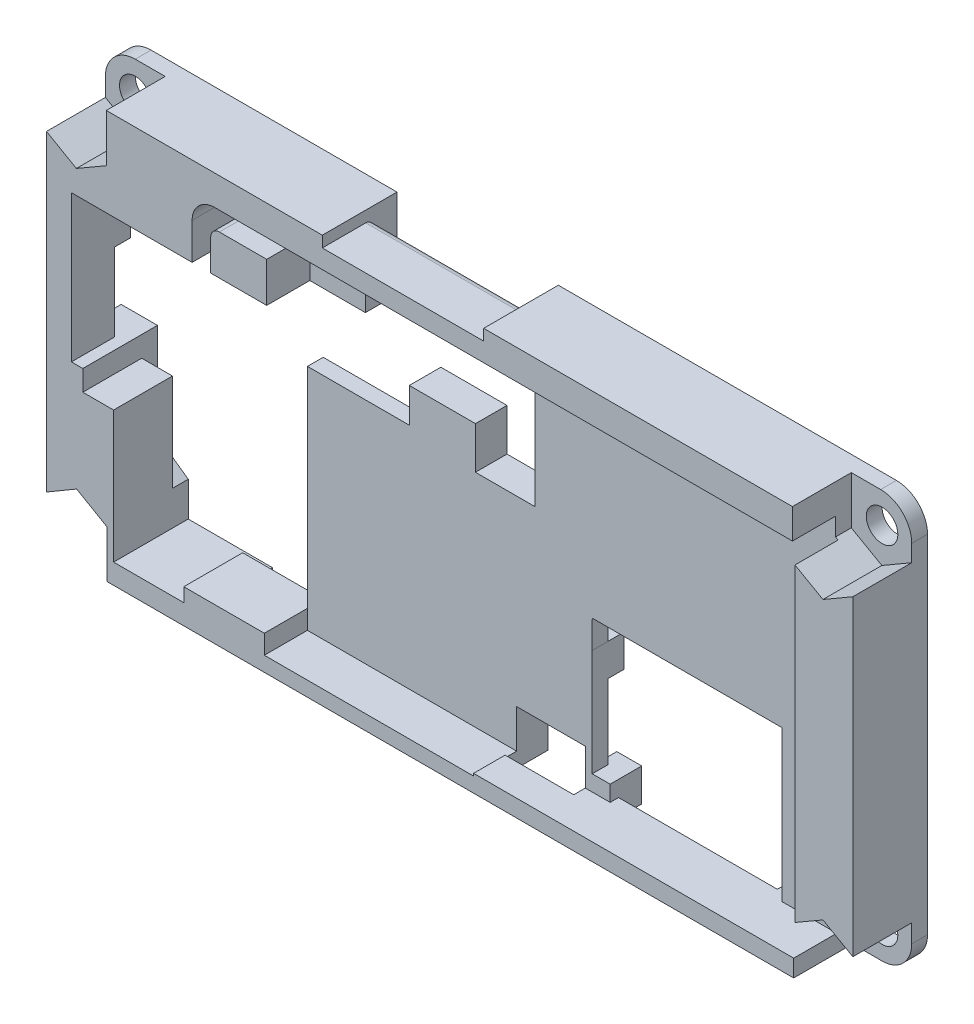
SolidWorks part; units mm, degrees
ref_plane "前视基准面" through (0, 0, 0) normal (0, 0, 1) x (1, 0, 0)
ref_plane "上视基准面" through (0, 0, 0) normal (0, 1, 0) x (1, 0, 0)
ref_plane "右视基准面" through (0, 0, 0) normal (1, 0, 0) x (0, 0, -1)
other "Configuration Table"
sketch "草图1" plane through (0, 0, 0) normal (0, 0, 1) x (1, 0, 0)
  line L0 (42.3742, 38.777) -> (73.7375, 38.777)
  line L1 (2.8575, 38.777) -> (73.7375, 38.777) construction
  line L2 (76.6955, 35.8191) -> (76.6955, 2.8364)
  line L3 (73.8718, 0.0127) -> (65.8565, 0.0127)
  line L4 (73.8718, 0.0127) -> (2.882, 0.0127) construction
  line L5 (65.8565, 0.0127) -> (65.8565, 13.0447)
  line L6 (65.8565, 13.0447) -> (70.1007, 13.0447)
  line L7 (70.1007, 13.0447) -> (70.1007, 20.0542)
  line L8 (70.1007, 20.0542) -> (44.7517, 20.0542)
  line L9 (44.7517, 22.4295) -> (44.7517, 32.4704)
  line L10 (44.7517, 32.4704) -> (42.3742, 32.4704)
  line L11 (42.3742, 32.4704) -> (42.3742, 38.777)
  line L12 (20.8324, 0.0127) -> (2.882, 0.0127)
  line L13 (0.0127, 2.882) -> (0.0127, 16.4108)
  line L14 (0.0127, 2.882) -> (0.0127, 35.9322) construction
  line L15 (0.0127, 16.4108) -> (3.4684, 16.4108)
  line L16 (3.4684, 16.4108) -> (3.4684, 7.2908)
  line L17 (3.4684, 7.2908) -> (6.395, 5.2037)
  line L18 (6.395, 5.2037) -> (6.395, 1.925)
  line L19 (6.395, 1.925) -> (14.4152, 1.925)
  line L20 (14.4152, 1.925) -> (14.4152, 1.4675)
  line L21 (14.4152, 1.4675) -> (20.8324, 1.4675)
  line L23 (2.8575, 38.777) -> (26.2427, 38.777)
  line L24 (26.2427, 38.777) -> (26.2427, 30.3451)
  line L25 (26.2427, 30.3451) -> (2.3856, 30.3451)
  line L26 (2.3856, 30.3451) -> (2.3856, 30.8342)
  line L27 (2.3856, 30.8342) -> (0.0127, 30.8342)
  line L28 (0.0127, 30.8342) -> (0.0127, 35.9322)
  line L29 (30.4158, 26.4371) -> (36.7059, 26.4371)
  line L30 (42.3742, 13.309) -> (47.8085, 13.309)
  line L31 (42.3742, 13.309) -> (42.3742, 10.2399)
  line L32 (42.3742, 10.2399) -> (47.8085, 10.2399)
  line L33 (47.8085, 13.309) -> (47.8085, 10.2399)
  line L34 (49.5154, 3.1504) -> (47.1508, 3.1504)
  line L35 (49.5154, 3.1504) -> (49.5154, 0.0127)
  line L36 (49.5154, 0.0127) -> (47.1508, 0.0127)
  line L37 (47.1508, 3.1504) -> (47.1508, 0.0127)
  line L38 (36.7059, 26.4371) -> (36.7059, 22.4295)
  line L39 (36.7059, 22.4295) -> (44.7517, 22.4295)
  line L40 (44.7517, 20.0542) -> (44.7517, 16.7907)
  line L41 (44.7517, 16.7907) -> (30.4158, 16.7907)
  line L42 (30.4158, 16.7907) -> (30.4158, 26.4371)
  line L44 (33.5959, 0.0127) -> (40.6267, 0.0127)
  line L45 (33.5959, 1.4675) -> (33.5959, 4.6376)
  line L46 (33.5959, 4.6376) -> (40.6267, 4.6376)
  line L47 (40.6267, 0.0127) -> (40.6267, 4.6376)
  line L48 (33.5959, 0.0127) -> (20.8324, 0.0127)
  line L50 (33.5959, 1.4675) -> (20.8324, 1.4675)
  arc A0 (73.7375, 38.777) -> (76.6955, 35.8191) centre (73.7375, 35.8191) cw
  arc A1 (76.6955, 2.8364) -> (73.8718, 0.0127) centre (73.8718, 2.8364) cw
  circle A2 centre (73.8718, 2.882) radius 1.5
  circle A3 centre (73.8718, 35.8941) radius 1.5
  arc A4 (2.882, 0.0127) -> (0.0127, 2.882) centre (2.882, 2.882) cw
  circle A5 centre (2.9024, 2.882) radius 1.5
  arc A6 (0.0127, 35.9322) -> (2.8575, 38.777) centre (2.8575, 35.9322) cw
  circle A7 centre (2.8575, 35.8776) radius 1.5
  dimension "D1" = 3
  dimension "D2" = 3
  dimension "D3" = 3
  dimension "D4" = 3
extrude "凸台-拉伸1" add sketch "草图1" along normal blind 1.5
sketch "草图3" plane through (0, 0, 1.5) normal (0, 0, 1) x (1, 0, 0)
  line L0 (0.0127, 35.9322) -> (0.0127, 30.8342) construction
  line L1 (26.2427, 38.777) -> (2.8575, 38.777) construction
  line L2 (0.0127, 34.2052) -> (0.0127, 30.8342)
  line L3 (26.2427, 38.777) -> (5.7019, 38.777)
  line L4 (26.2427, 38.777) -> (26.2427, 30.3451)
  line L5 (26.2427, 30.3451) -> (2.3856, 30.3451)
  line L6 (2.3856, 30.3451) -> (2.3856, 23.8174)
  line L7 (2.3856, 23.8174) -> (0.0127, 23.8174)
  line L8 (0.0127, 2.882) -> (0.0127, 35.9322) construction
  line L9 (0.0127, 23.8174) -> (0.0127, 30.8342)
  line L10 (5.7019, 38.777) -> (5.7019, 34.2258)
  line L11 (5.7019, 34.2258) -> (2.8575, 32.5779)
  line L12 (2.8575, 32.5779) -> (0.0127, 34.2052)
  line L13 (42.3742, 38.777) -> (70.9493, 38.777)
  line L14 (73.7375, 38.777) -> (42.3742, 38.777) construction
  line L15 (70.9493, 38.777) -> (70.9493, 34.2258)
  line L16 (70.9493, 34.2258) -> (73.8524, 32.5779)
  line L17 (73.8524, 32.5779) -> (76.6955, 34.2258)
  line L18 (76.6955, 35.8191) -> (76.6955, 2.8364) construction
  line L19 (76.6955, 34.2258) -> (76.6955, 4.5742)
  line L20 (76.6955, 2.8364) -> (76.6955, 35.8191) construction
  line L21 (76.6955, 4.5742) -> (73.8524, 6.188)
  line L22 (73.8524, 6.188) -> (71.0683, 4.5742)
  line L23 (71.0683, 4.5742) -> (71.0683, 0.0127)
  line L24 (65.8565, 0.0127) -> (73.8718, 0.0127) construction
  line L25 (71.0683, 0.0127) -> (65.8565, 0.0127)
  line L26 (65.8565, 0.0127) -> (65.8565, 13.0447)
  line L27 (65.8565, 13.0447) -> (65.8565, 15.9725)
  line L28 (65.8565, 15.9725) -> (47.8131, 15.9725)
  line L29 (47.8131, 15.9725) -> (47.8085, 13.309)
  line L30 (47.8085, 13.309) -> (47.8085, 3.1504)
  line L31 (49.5154, 3.1504) -> (47.1508, 3.1504) construction
  line L32 (47.8085, 3.1504) -> (49.5154, 3.1504)
  line L33 (49.5154, 3.1504) -> (49.5154, 0.0127)
  line L34 (49.5154, 0.0127) -> (47.1508, 0.0127)
  line L35 (47.1508, 0.0127) -> (47.1508, 5.0962)
  line L36 (47.1508, 5.0962) -> (42.3742, 5.0962)
  line L39 (0.0127, 16.4108) -> (3.4684, 16.4108)
  line L40 (3.4684, 16.4108) -> (0.0127, 16.4108) construction
  line L41 (3.4684, 16.4108) -> (3.4684, 14.453)
  line L42 (3.4684, 7.2908) -> (3.4684, 16.4108) construction
  line L43 (3.4684, 14.453) -> (6.395, 14.453)
  line L44 (6.395, 14.453) -> (6.395, 10.1048)
  line L45 (6.395, 10.1048) -> (6.395, 5.2037)
  line L46 (6.395, 5.2037) -> (6.395, 1.925)
  line L47 (6.395, 1.925) -> (13.0684, 1.925)
  line L48 (14.4152, 1.925) -> (6.395, 1.925) construction
  line L49 (13.0684, 1.925) -> (13.0684, 3.2369)
  line L50 (13.0684, 3.2369) -> (20.728, 3.2369)
  line L52 (40.0567, 0.0127) -> (5.7831, 0.0127)
  line L53 (2.882, 0.0127) -> (40.6267, 0.0127) construction
  line L54 (5.7831, 0.0127) -> (5.7831, 4.506)
  line L55 (5.7831, 4.506) -> (2.882, 6.188)
  line L56 (2.882, 6.188) -> (0.0127, 4.506)
  line L57 (0.0127, 4.506) -> (0.0127, 16.4108)
  line L58 (42.3742, 22.4295) -> (36.7059, 22.4295)
  line L59 (44.7517, 22.4295) -> (36.7059, 22.4295) construction
  line L60 (36.7059, 22.4295) -> (36.7059, 26.4371)
  line L61 (36.7059, 26.4371) -> (30.4158, 26.4371)
  line L62 (30.4158, 26.4371) -> (30.4158, 23.1633)
  line L66 (42.3742, 22.4295) -> (42.3742, 38.777)
  line L67 (40.6267, 0.0127) -> (40.6267, 4.6376)
  line L68 (40.6267, 4.6376) -> (40.6267, 5.0962)
  line L69 (40.6267, 5.0962) -> (42.3742, 5.0962)
  line L70 (40.0567, 0.0127) -> (40.6267, 0.0127)
  line L71 (20.728, 3.2369) -> (20.728, 23.1633)
  line L72 (32.6413, 23.1633) -> (15.9072, 23.1633) construction
  line L73 (20.728, 23.1633) -> (30.4158, 23.1633)
extrude "凸台-拉伸2" add sketch "草图3" along normal blind 1.5
sketch "草图5" plane through (0, 0, 3) normal (0, 0, 1) x (1, 0, 0)
  line L0 (42.3742, 38.777) -> (42.3742, 22.4295) construction
  line L1 (70.9493, 38.777) -> (42.3742, 38.777)
  line L2 (70.9493, 38.777) -> (70.9493, 35.9391)
  line L3 (70.9493, 35.9391) -> (42.3742, 35.9391)
  line L4 (42.3742, 38.777) -> (42.3742, 35.9391)
  line L5 (76.6955, 34.2258) -> (73.8524, 32.5779)
  line L6 (73.8524, 32.5779) -> (71.1891, 34.0897)
  line L7 (73.8524, 32.5779) -> (70.9493, 34.2258) construction
  line L8 (71.1891, 34.0897) -> (71.1891, 4.6442)
  line L9 (71.0683, 4.5742) -> (73.8524, 6.188) construction
  line L10 (71.1891, 4.6442) -> (73.8524, 6.188)
  line L11 (73.8524, 6.188) -> (76.6955, 4.5742)
  line L12 (76.6955, 4.5742) -> (76.6955, 34.2258)
  line L13 (47.1508, 5.0962) -> (47.1508, 0.0127) construction
  line L14 (71.0683, 0.0127) -> (47.1508, 0.0127)
  line L15 (71.0683, 0.0127) -> (71.0683, 1.6475)
  line L16 (71.0683, 1.6475) -> (47.1508, 1.6475)
  line L17 (47.1508, 0.0127) -> (47.1508, 1.6475)
  line L19 (40.6267, 0.0127) -> (6.395, 0.0127)
  line L20 (40.6267, 0.0127) -> (40.6267, 1.423)
  line L21 (40.6267, 1.423) -> (20.728, 1.423)
  line L23 (6.395, 1.925) -> (13.0684, 1.925)
  line L24 (13.0684, 1.925) -> (13.0684, 3.2369)
  line L25 (13.0684, 3.2369) -> (20.728, 3.2369)
  line L26 (20.728, 3.2369) -> (20.728, 1.423)
  line L27 (26.2427, 38.777) -> (26.2427, 35.9391)
  line L28 (26.2427, 30.3451) -> (26.2427, 38.777) construction
  line L29 (26.2427, 35.9391) -> (20.9533, 35.9391)
  line L30 (20.9533, 35.9391) -> (20.9533, 30.3451)
  line L31 (2.3856, 30.3451) -> (26.2427, 30.3451) construction
  line L32 (20.9533, 30.3451) -> (2.3856, 30.3451)
  line L33 (2.3856, 30.3451) -> (2.3856, 23.8174)
  line L35 (0.0127, 23.8174) -> (0.0127, 34.2052)
  line L36 (0.0127, 34.2052) -> (2.8575, 32.5779)
  line L37 (2.8575, 32.5779) -> (5.7019, 34.2258)
  line L38 (5.7019, 34.2258) -> (5.7019, 38.777)
  line L39 (5.7019, 38.777) -> (26.2427, 38.777)
  line L40 (6.395, 0.0127) -> (5.7831, 0.0127)
  line L41 (5.7831, 0.0127) -> (5.7831, 4.506)
  line L42 (5.7831, 4.506) -> (2.882, 6.188)
  line L43 (2.882, 6.188) -> (0.0127, 4.506)
  line L44 (0.0127, 4.506) -> (0.0127, 16.4108)
  line L45 (0.0127, 16.4108) -> (0.0127, 23.8174)
  line L46 (2.3856, 23.8174) -> (2.3856, 16.4108)
  line L47 (3.4684, 16.4108) -> (0.0127, 16.4108) construction
  line L48 (2.3856, 16.4108) -> (3.4684, 16.4108)
  line L49 (3.4684, 16.4108) -> (3.4684, 14.453)
  line L50 (3.4684, 14.453) -> (6.395, 14.453)
  line L51 (6.395, 14.453) -> (6.395, 1.925)
extrude "凸台-拉伸3" add sketch "草图5" along normal blind 4.1
sketch "草图6" plane through (0, 38.777, 0) normal (0, 1, 0) x (1, 0, 0)
  line L0 (44.7517, 0) -> (36.7059, 0) construction
  line L1 (42.3742, -7.1) -> (41.5867, -7.1)
  line L2 (42.3742, -7.1) -> (42.3742, 0)
  line L3 (42.3742, 0) -> (41.5867, 0)
  line L4 (41.5867, -7.1) -> (41.5867, 0)
  line L5 (41.5867, -7.1) -> (41.5867, -11.5) construction
extrude "凸台-拉伸4" add sketch "草图6" against normal up to surface (2.8379 mm away) up to face at (56.6617, 35.9391, 5.05)
sketch "草图7" plane through (41.5867, 0, 0) normal (-1, 0, 0) x (0, 0, 1)
  line L0 (7.1, 35.9391) -> (2.2691, 35.9391)
  line L1 (7.1, 35.9391) -> (0, 35.9391) construction
  line L2 (2.2691, 35.9391) -> (2.2691, 37.0224)
  line L3 (8.3493, 37.7224) -> (1.2875, 37.7224) construction
  line L4 (7.1, 37.7224) -> (9.4, 37.7224) construction
  line L5 (2.9691, 37.7224) -> (7.1, 37.7224)
  line L6 (7.1, 35.9391) -> (7.1, 38.777) construction
  line L7 (7.1, 37.7224) -> (7.1, 35.9391)
  arc A0 (2.2691, 37.0224) -> (2.9691, 37.7224) centre (2.9691, 37.0224) cw
extrude "凸台-拉伸5" add sketch "草图7" along normal up to surface (15.344 mm away) up to face at (26.2427, 35.0204, 3.3667)
sketch "草图8" plane through (0, 0, 7.1) normal (0, 0, 1) x (1, 0, 0)
  line L0 (20.9533, 35.9391) -> (15.9921, 35.9391)
  line L1 (13.8622, 33.8093) -> (13.8622, 30.3451)
  line L2 (2.3856, 30.3451) -> (20.9533, 30.3451) construction
  line L3 (13.8622, 30.3451) -> (15.6321, 30.3451)
  line L4 (15.6321, 30.3451) -> (15.6321, 33.3218)
  line L5 (16.4533, 34.143) -> (20.9533, 34.143)
  line L6 (20.9533, 30.3451) -> (20.9533, 35.9391) construction
  line L7 (20.9533, 34.143) -> (20.9533, 35.9391)
  arc A0 (15.9921, 35.9391) -> (13.8622, 33.8093) centre (15.9921, 33.8093) ccw
  arc A1 (15.6321, 33.3218) -> (16.4533, 34.143) centre (16.4533, 33.3218) cw
extrude "切除-拉伸1" cut sketch "草图8" against normal blind 4.1
sketch "草图9" plane through (0, 0.0127, 0) normal (0, -1, 0) x (1, 0, 0)
  line L0 (49.5154, 2.2038) -> (64.6151, 2.2038)
  line L1 (49.5154, 3) -> (49.5154, 0) construction
  line L2 (64.6151, 2.2038) -> (64.6151, 0)
  line L3 (44.7517, 0) -> (70.1007, 0) construction
  line L4 (64.6151, 0) -> (65.8565, 0)
  line L5 (65.8565, 0) -> (65.8565, 3)
  line L6 (65.8565, 3) -> (49.5154, 3)
  line L7 (49.5154, 3) -> (49.5154, 2.2038)
extrude "凸台-拉伸6" add sketch "草图9" against normal up to surface (1.6348 mm away) up to face at (58.635, 1.6475, 4.3667)
sketch "草图10" plane through (0, 0.0127, 0) normal (0, -1, 0) x (1, 0, 0)
  line L0 (47.1508, 7.1) -> (47.1508, 0) construction
  line L1 (40.6267, 7.1) -> (47.1508, 7.1)
  line L2 (40.6267, 7.1) -> (40.6267, 4.1)
  line L3 (40.6267, 4.1) -> (47.1508, 4.1)
  line L4 (47.1508, 7.1) -> (47.1508, 4.1)
  dimension "D1" = 3
extrude "凸台-拉伸7" add sketch "草图10" against normal up to surface (1.6348 mm away) up to face at (59.6412, 1.6475, 3.0608)
